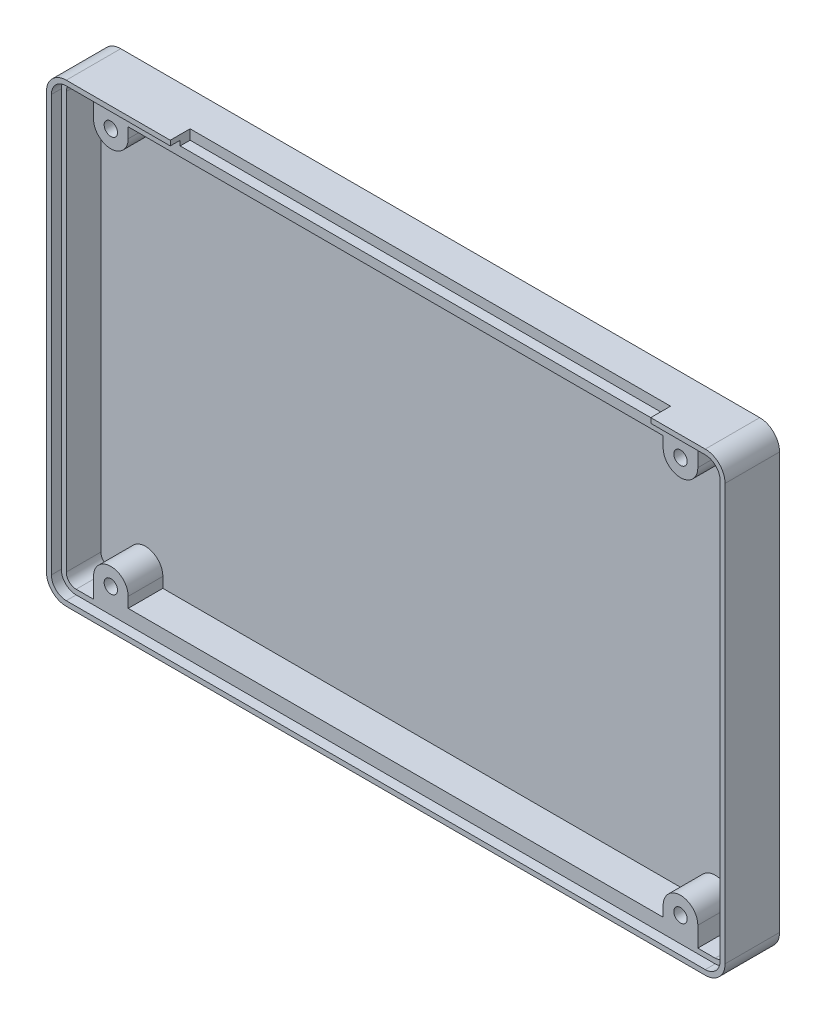
SolidWorks part; units mm, degrees
ref_plane "Front Plane" through (0, 0, 0) normal (0, 0, 1) x (1, 0, 0)
ref_plane "Top Plane" through (0, 0, 0) normal (0, 1, 0) x (1, 0, 0)
ref_plane "Right Plane" through (0, 0, 0) normal (1, 0, 0) x (0, 0, -1)
sketch "Sketch1" plane through (0, 0, 0) normal (0, 0, 1) x (1, 0, 0)
  line L1 (0, 0) -> (137, 0)
  line L2 (0, 0) -> (0, 92)
  line L3 (0, 92) -> (137, 92)
  line L4 (137, 0) -> (137, 92)
  dimension "D1" = 137
  dimension "D2" = 92
extrude "Boss-Extrude1" add sketch "Sketch1" along normal blind 2
sketch "Sketch2" plane through (0, 0, 2) normal (0, 0, 1) x (1, 0, 0)
  line L1 (0, 92) -> (137, 92)
  line L2 (0, 92) -> (0, 0)
  line L3 (0, 0) -> (137, 0)
  line L4 (137, 92) -> (137, 0)
  line L5 (2, 2) -> (135, 2)
  line L6 (2, 2) -> (2, 90)
  line L7 (2, 90) -> (135, 90)
  line L8 (135, 2) -> (135, 90)
  dimension "D1" = 2
  dimension "D2" = 2
  dimension "D3" = 2
  dimension "D4" = 2
extrude "Boss-Extrude2" add sketch "Sketch2" along normal blind 7
sketch "Sketch3" plane through (0, 0, 9) normal (0, 0, 1) x (1, 0, 0)
  line L1 (0, 0) -> (137, 0)
  line L2 (0, 0) -> (0, 92)
  line L3 (0, 92) -> (137, 92)
  line L4 (137, 0) -> (137, 92)
  line L5 (1, 1) -> (136, 1)
  line L6 (1, 1) -> (1, 91)
  line L7 (1, 91) -> (136, 91)
  line L8 (136, 1) -> (136, 91)
  dimension "D1" = 1
  dimension "D2" = 1
  dimension "D3" = 1
  dimension "D4" = 1
extrude "Boss-Extrude3" add sketch "Sketch3" along normal blind 2
sketch "Sketch4" plane through (0, 0, 2) normal (0, 0, 1) x (1, 0, 0)
  line L0 (0, 0) -> (137, 0) construction
  line L1 (0, 92) -> (0, 0) construction
  line L2 (2, 2) -> (135, 2) construction
  line L4 (7.5, 6) -> (7.5, 2)
  line L5 (7.5, 2) -> (14.5, 2)
  line L6 (14.5, 6) -> (14.5, 2)
  line L7 (137, 0) -> (137, 92) construction
  line L8 (137, 92) -> (0, 92) construction
  line L9 (2, 2) -> (135, 2) construction
  line L11 (122.5, 6) -> (122.5, 2)
  line L12 (122.5, 2) -> (129.5, 2)
  line L13 (129.5, 6) -> (129.5, 2)
  line L14 (135, 90) -> (2, 90) construction
  line L16 (129.5, 86) -> (129.5, 90)
  line L17 (129.5, 90) -> (122.5, 90)
  line L18 (122.5, 86) -> (122.5, 90)
  line L19 (135, 90) -> (2, 90) construction
  line L21 (14.5, 86) -> (14.5, 90)
  line L22 (14.5, 90) -> (7.5, 90)
  line L23 (7.5, 86) -> (7.5, 90)
  arc A0 (14.5, 6) -> (7.5, 6) centre (11, 6) ccw
  circle A1 centre (11, 6) radius 1.35
  arc A2 (7.5, 86) -> (14.5, 86) centre (11, 86) ccw
  circle A3 centre (11, 86) radius 1.35
  arc A4 (122.5, 86) -> (129.5, 86) centre (126, 86) ccw
  circle A5 centre (126, 86) radius 1.35
  arc A6 (129.5, 6) -> (122.5, 6) centre (126, 6) ccw
  circle A7 centre (126, 6) radius 1.35
  dimension "D1" = 2.7
  dimension "D2" = 7
  dimension "D3" = 2.7
  dimension "D4" = 7
  dimension "D5" = 2.7
  dimension "D6" = 7
  dimension "D7" = 2.7
  dimension "D8" = 7
  dimension "D11" = 6
  dimension "D9" = 6
  dimension "D10" = 11
  dimension "D12" = 11
  dimension "D13" = 11
  dimension "D14" = 6
  dimension "D15" = 11
  dimension "D16" = 6
extrude "Boss-Extrude4" add sketch "Sketch4" along normal blind 7
sketch "Sketch8" plane through (0, 0, 2) normal (0, 0, 1) x (1, 0, 0)
  line L0 (122.5, 6) -> (122.5, 2) construction
  line L1 (14.5, 2) -> (122.5, 2)
  line L2 (14.5, 2) -> (14.5, 3.9)
  line L3 (14.5, 3.9) -> (122.5, 3.9)
  line L4 (122.5, 2) -> (122.5, 3.9)
  dimension "D1" = 1.9
extrude "Boss-Extrude6" add sketch "Sketch8" along normal blind 7
fillet "Fillet1" radius 2 4 edges at (2, 2, 5.5) (135, 2, 5.5) (135, 90, 5.5) (2, 90, 5.5)
fillet "Fillet2" radius 3 4 edges at (1, 1, 10) (136, 1, 10) (136, 91, 10) (1, 91, 10)
fillet "Fillet3" radius 4 4 edges at (137, 92, 5.5) (0, 92, 5.5) (0, 0, 5.5) (137, 0, 5.5)
sketch "Sketch11" plane through (0, 0, 2) normal (0, 0, 1) x (1, 0, 0)
  line L0 (122.5, 90) -> (122.5, 86) construction
  line L1 (14.5, 90) -> (122.5, 90)
  line L2 (14.5, 90) -> (14.5, 88.1)
  line L3 (14.5, 88.1) -> (122.5, 88.1)
  line L4 (122.5, 90) -> (122.5, 88.1)
  dimension "D1" = 1.9
extrude "Boss-Extrude7" add sketch "Sketch11" along normal blind 7
sketch "Sketch12" plane through (0, 92, 0) normal (0, 1, 0) x (1, 0, 0)
  line L0 (133, -11) -> (4, -11) construction
  line L1 (25, -11) -> (122, -11)
  line L2 (25, -11) -> (25, -7)
  line L3 (25, -7) -> (122, -7)
  line L4 (122, -11) -> (122, -7)
  line L5 (0, -11) -> (0, 0) construction
  dimension "D1" = 4
  dimension "D2" = 97
  dimension "D3" = 25
extrude "Cut-Extrude3" cut sketch "Sketch12" against normal blind 2
sketch "Sketch13" plane through (0, 0, 9) normal (0, 0, 1) x (1, 0, 0)
  circle A0 centre (11, 86) radius 1.35
  circle A1 centre (11, 6) radius 1.35
  circle A2 centre (126, 6) radius 1.35
  circle A3 centre (126, 86) radius 1.35
  dimension "D1" = 2.7
  dimension "D2" = 2.7
  dimension "D3" = 2.7
  dimension "D4" = 2.7
extrude "Cut-Extrude4" cut sketch "Sketch13" against normal blind 10
